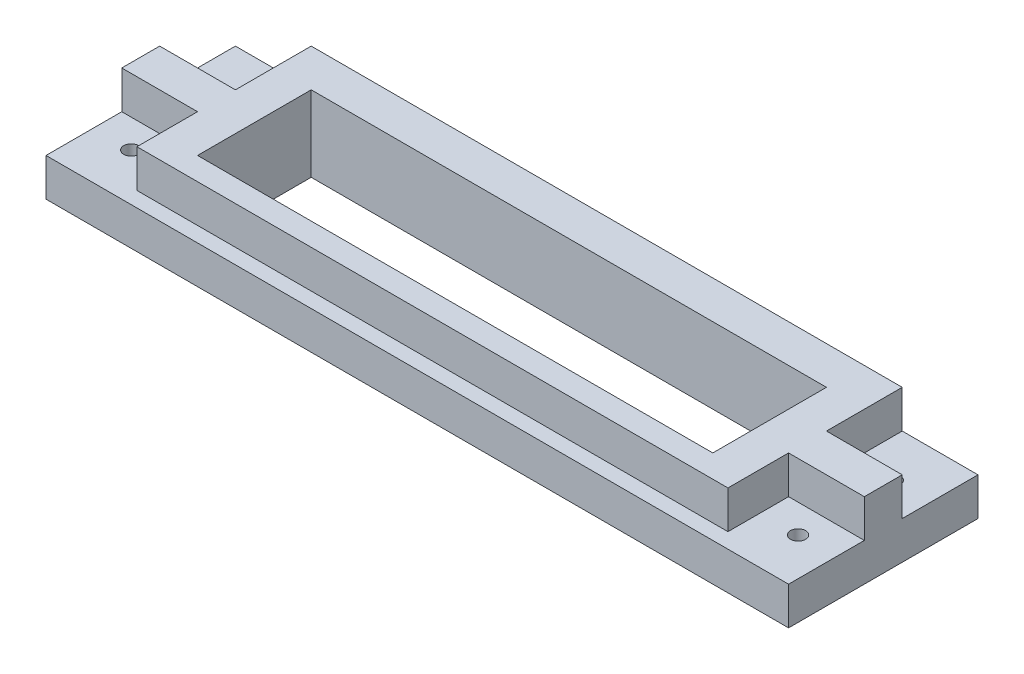
SolidWorks part; units mm, degrees
ref_plane "Front Plane" through (0, 0, 0) normal (0, 0, 1) x (1, 0, 0)
ref_plane "Top Plane" through (0, 0, 0) normal (0, 1, 0) x (1, 0, 0)
ref_plane "Right Plane" through (0, 0, 0) normal (1, 0, 0) x (0, 0, -1)
sketch "Sketch1" plane through (0, 0, 0) normal (0, 1, 0) x (1, 0, 0)
  line L1 (-39, 12.5) -> (39, 12.5)
  line L2 (-39, 12.5) -> (-39, -12.5)
  line L3 (-39, -12.5) -> (39, -12.5)
  line L4 (39, 12.5) -> (39, -12.5)
  line L5 (-39, 12.5) -> (39, -12.5) construction
  line L6 (-39, -12.5) -> (39, 12.5) construction
  point P0 (0, 0)
  dimension "D1" = 78
  dimension "D2" = 25
extrude "Boss-Extrude1" add sketch "Sketch1" along normal blind 10
sketch "Sketch2" plane through (0, 10, 0) normal (0, 1, 0) x (1, 0, 0)
  line L0 (0, 12.5) -> (0, 7.5)
  line L1 (39, 12.5) -> (-39, 12.5) construction
  line L2 (-39, 0) -> (-34, 0)
  line L3 (-39, 12.5) -> (-39, -12.5) construction
  line L9 (34, -7.5) -> (-34, -7.5)
  line L10 (34, -7.5) -> (34, 7.5)
  line L11 (34, 7.5) -> (-34, 7.5)
  line L12 (-34, -7.5) -> (-34, 7.5)
  line L13 (34, -7.5) -> (-34, 7.5) construction
  line L14 (34, 7.5) -> (-34, -7.5) construction
  point P9 (0, 0)
  point P10 (0, 0)
extrude "Cut-Extrude2" cut sketch "Sketch2" against normal blind 10 contours L12 L9 L10 L11
sketch "Sketch3" plane through (-39, 0, 0) normal (-1, 0, 0) x (0, 0, 1)
  line L0 (-12.5, 0) -> (-12.5, 5)
  line L1 (-12.5, 10) -> (-12.5, 0) construction
  line L2 (-12.5, 5) -> (12.5, 5)
  line L3 (12.5, 10) -> (12.5, 0) construction
  line L4 (12.5, 5) -> (12.5, 0)
  line L5 (12.5, 0) -> (-12.5, 0)
extrude "Boss-Extrude2" add sketch "Sketch3" along normal blind 10
sketch "Sketch4" plane through (39, 0, 0) normal (1, 0, 0) x (0, 0, -1)
  line L1 (-12.5, 5) -> (12.5, 5)
  line L2 (-12.5, 5) -> (-12.5, 0)
  line L3 (-12.5, 0) -> (12.5, 0)
  line L4 (12.5, 5) -> (12.5, 0)
extrude "Boss-Extrude3" add sketch "Sketch4" along normal blind 10
ref_plane "Plane1" through (0, 5, 0) normal (0, 1, 0) x (1, 0, 0)
sketch "Sketch6" plane through (0, 5, 0) normal (0, 1, 0) x (1, 0, 0)
  line L2 (39, 12.5) -> (39, -12.5) construction
  line L3 (-49, -2.5) -> (-39, -2.5)
  line L6 (49, 2.5) -> (49, -2.5)
  line L7 (49, -2.5) -> (39, -2.5)
  line L8 (39, -2.5) -> (39, 2.5)
  line L9 (49, 2.5) -> (39, 2.5)
  line L10 (0, -7.5) -> (0, -2.5)
  line L11 (34, -7.5) -> (-34, -7.5) construction
  line L12 (-49, 2.5) -> (-49, -2.5)
  line L13 (-49, 2.5) -> (-39, 2.5)
  line L14 (-39, -2.5) -> (-39, 2.5)
extrude "Boss-Extrude4" add sketch "Sketch6" along normal blind 5 contours L6 L9 L8 L7 | L3 L14 L13 L12
sketch "Sketch9" plane through (0, 0, 0) normal (0, -1, 0) x (1, 0, 0)
  line L0 (49, -12.5) -> (-49, -12.5) construction
  line L1 (-49, 12.5) -> (-39, 12.5) construction
  line L2 (-49, 12.5) -> (-49, -12.5) construction
  line L3 (-49, -12.5) -> (-39, -12.5) construction
  line L4 (-39, 12.5) -> (-39, -12.5) construction
  line L5 (-44, 12.5) -> (-44, 0) construction
  line L6 (-44, 0) -> (-41.3729, 0)
  line L7 (0, 7.5) -> (0, 4.835)
  line L8 (34, 7.5) -> (-34, 7.5) construction
  circle A0 centre (-44, 6.25) radius 1.75
  circle A1 centre (-44, -6.25) radius 1.75
  circle A2 centre (44, -6.25) radius 1.75
  circle A3 centre (44, 6.25) radius 1.75
  dimension "D1" = 3.5
extrude "Cut-Extrude5" cut sketch "Sketch9" against normal blind 2 contours A0 | A1 | A3 | A2
sketch "Sketch10" plane through (0, 2, 0) normal (0, -1, 0) x (1, 0, 0)
  line L0 (-49, 0) -> (-47.2279, 0)
  line L1 (-49, -12.5) -> (-49, 12.5) construction
  line L2 (0, -7.5) -> (0, -5.5971)
  line L3 (34, -7.5) -> (-34, -7.5) construction
  circle A0 centre (-44, 6.25) radius 1
  circle A1 centre (-44, -6.25) radius 1
  circle A2 centre (44, -6.25) radius 1
  circle A3 centre (44, 6.25) radius 1
  point P18 (0, 0)
extrude "Cut-Extrude6" cut sketch "Sketch10" against normal blind 13 contours A0 | A1 | A3 | A2
sketch "Sketch11" plane through (0, 0, 12.5) normal (0, 0, 1) x (1, 0, 0)
  line L1 (39, 10) -> (-39, 10)
  line L2 (39, 10) -> (39, 5)
  line L3 (39, 5) -> (-39, 5)
  line L4 (-39, 10) -> (-39, 5)
extrude "Cut-Extrude7" cut sketch "Sketch11" against normal blind 2
